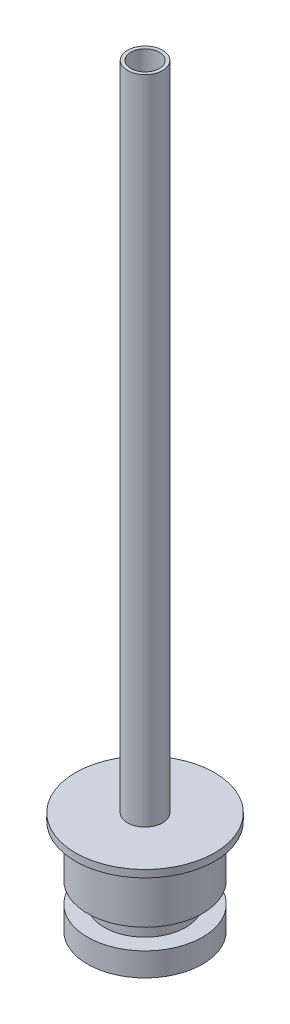
SolidWorks part; units mm, degrees
ref_plane "Front Plane" through (0, 0, 0) normal (0, 0, 1) x (1, 0, 0)
ref_plane "Top Plane" through (0, 0, 0) normal (0, 1, 0) x (1, 0, 0)
ref_plane "Right Plane" through (0, 0, 0) normal (1, 0, 0) x (0, 0, -1)
sketch "Sketch1" plane through (0, 0, 0) normal (0, 1, 0) x (1, 0, 0)
  circle A0 centre (0, 0) radius 9.5
  dimension "D1" = 19
extrude "Boss-Extrude1" add sketch "Sketch1" along normal blind 14
sketch "Sketch2" plane through (0, 14, 0) normal (0, 1, 0) x (1, 0, 0)
  circle A0 centre (0, 0) radius 2.4
  dimension "D1" = 4.8
extrude "Boss-Extrude2" add sketch "Sketch2" along normal offset from surface (89 mm away) 103 up to face at (0, 0, 9.5)
sketch "Sketch3" plane through (0, 103, 0) normal (0, 1, 0) x (1, 0, 0)
  circle A0 centre (0, 0) radius 1.94
  circle A1 centre (0, 0) radius 2.4 construction
  dimension "D1" = 0.46
extrude "Cut-Extrude1" cut sketch "Sketch3" against normal through all
sketch "Sketch4" plane through (0, 0, 0) normal (0, -1, 0) x (1, 0, 0)
  circle A0 centre (0, 0) radius 9.5 construction
  circle A1 centre (0, 0) radius 9.5
  circle A2 centre (0, 0) radius 7.85
  dimension "D1" = 15.7
extrude "Cut-Extrude2" cut sketch "Sketch4" against normal blind 13
sketch "Sketch5" plane through (0, 0, 0) normal (0, -1, 0) x (1, 0, 0)
  circle A0 centre (0, 0) radius 5.55
  circle A1 centre (0, 0) radius 7.85 construction
  circle A2 centre (0, 0) radius 7.85
  dimension "D1" = 11.1
extrude "Cut-Extrude3" cut sketch "Sketch5" against normal blind 2.8 from offset 3.2
